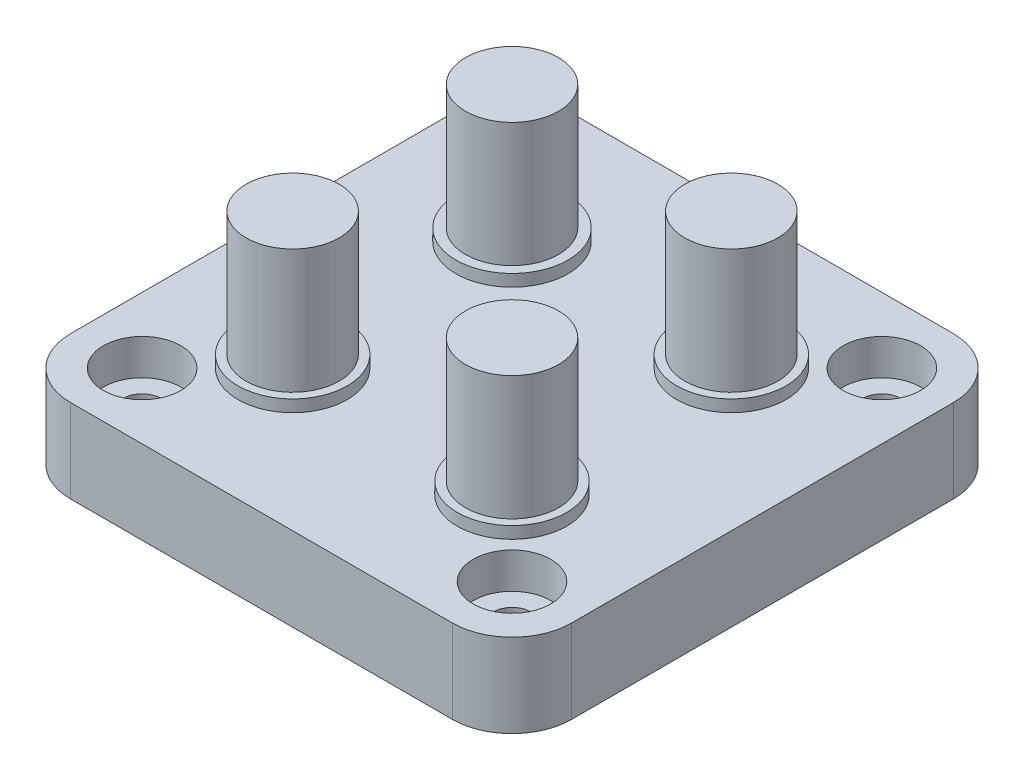
SolidWorks part; units mm, degrees
ref_plane "Ebene vorne" through (0, 0, 0) normal (0, 0, 1) x (1, 0, 0)
ref_plane "Ebene oben" through (0, 0, 0) normal (0, 1, 0) x (1, 0, 0)
ref_plane "Ebene rechts" through (0, 0, 0) normal (1, 0, 0) x (0, 0, -1)
sketch "Skizze1" plane through (0, 0, 0) normal (0, 1, 0) x (1, 0, 0)
  line L1 (0, 0) -> (42, 0)
  line L2 (0, 0) -> (0, 42)
  line L3 (0, 42) -> (42, 42)
  line L4 (42, 0) -> (42, 42)
  line L5 (0, 0) -> (42, 42) construction
  line L6 (0, 42) -> (42, 0) construction
  circle A0 centre (5.5, 36.5) radius 1.6
  circle A1 centre (36.5, 36.5) radius 1.6
  circle A2 centre (5.5, 5.5) radius 1.6
  circle A3 centre (36.5, 5.5) radius 1.6
  circle A4 centre (21, 21) radius 3.5
  point P4 (21, 21)
  dimension "D2" = 3.2
  dimension "D4" = 7
  dimension "D1" = 42
  dimension "D3" = 31
extrude "Aufsatz-Linear austragen1" add sketch "Skizze1" along normal blind 7
sketch "Skizze2" plane through (0, 7, 0) normal (0, 1, 0) x (1, 0, 0)
  line L0 (0, 42) -> (42, 0) construction
  line L1 (0, 0) -> (42, 42) construction
  circle A0 centre (11.8076, 30.1924) radius 3.9
  circle A1 centre (30.1924, 30.1924) radius 3.9
  circle A2 centre (30.1924, 11.8076) radius 3.9
  circle A3 centre (11.8076, 11.8076) radius 3.9
  dimension "D1" = 7.8
  dimension "D2" = 26
extrude "Aufsatz-Linear austragen2" add sketch "Skizze2" along normal blind 11.4
fillet "Verrundung1" radius 5 4 edges at (0, 3.5, -42) (42, 3.5, -42) (42, 3.5, 0) (0, 3.5, 0)
sketch "Skizze3" plane through (0, 0, 0) normal (0, -1, 0) x (1, 0, 0)
  circle A0 centre (21, -21) radius 12
  dimension "D1" = 24
extrude "Schnitt-Linear austragen1" cut sketch "Skizze3" against normal blind 3
sketch "Skizze4" plane through (0, 7, 0) normal (0, 1, 0) x (1, 0, 0)
  circle A0 centre (5.5, 36.5) radius 3.25
  circle A1 centre (36.5, 36.5) radius 3.25
  circle A2 centre (5.5, 5.5) radius 3.25
  circle A3 centre (36.5, 5.5) radius 3.25
  dimension "D1" = 6.5
extrude "Schnitt-Linear austragen2" cut sketch "Skizze4" against normal blind 3
sketch "Skizze5" plane through (0, 7, 0) normal (0, 1, 0) x (1, 0, 0)
  circle A0 centre (11.8076, 30.1924) radius 4.7
  circle A1 centre (11.8076, 11.8076) radius 4.5805
  circle A2 centre (30.1924, 11.8076) radius 4.5805
  circle A3 centre (30.1924, 30.1924) radius 4.5805
  dimension "D1" = 9.4
extrude "Aufsatz-Linear austragen3" add sketch "Skizze5" along normal blind 1
